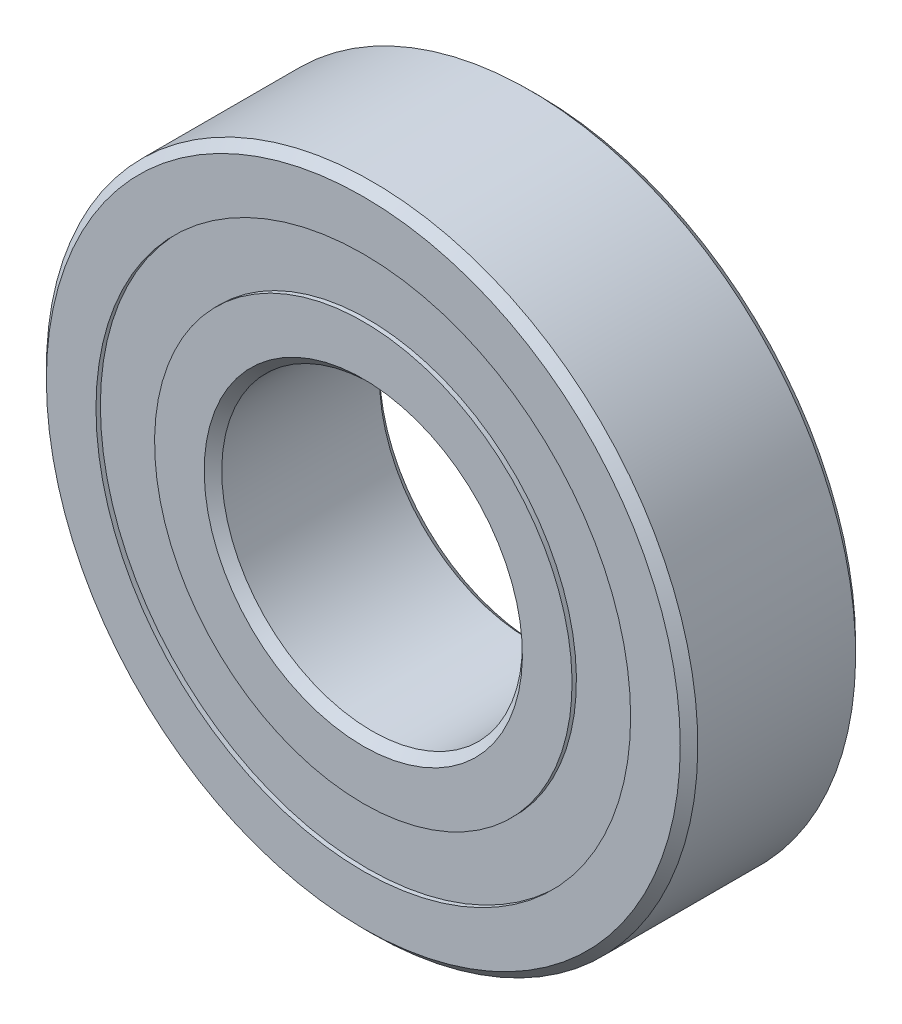
SolidWorks part; units mm, degrees
ref_plane "Front Plane" through (0, 0, 0) normal (0, 0, 1) x (1, 0, 0)
ref_plane "Top Plane" through (0, 0, 0) normal (0, 1, 0) x (1, 0, 0)
ref_plane "Right Plane" through (0, 0, 0) normal (1, 0, 0) x (0, 0, -1)
sketch "Sketch1" plane through (0, 0, 0) normal (0, 0, 1) x (1, 0, 0)
  line L0 (-20.6375, 0) -> (20.6375, 0) construction
  line L1 (-9.525, 0) -> (9.525, 0) construction
  circle A0 centre (0, 0) radius 9.525 construction
  circle A1 centre (0, 0) radius 20.6375 construction
  point P3 (0, 0)
  point P6 (0, 0)
  point P7 (0, -9.525)
  point P11 (0, -20.6375)
  point P12 (0, 9.525)
  point P13 (0, 20.6375)
  dimension "OD" = 41.275
  dimension "ID" = 19.05
sketch "SketchB" plane through (0, 0, 0) normal (1, 0, 0) x (0, 0, -1)
  line L0 (-5.5563, 20.6375) -> (5.5562, 20.6375) construction
  line L1 (0, 20.6375) -> (0, -20.6375) construction
  line L2 (5.0006, 20.6375) -> (-5.0006, 20.6375)
  line L3 (-5.0006, 20.6375) -> (-5.5563, 20.0819)
  line L4 (-5.5563, 20.0819) -> (-5.5563, 16.9374)
  line L5 (-5.5563, 16.9374) -> (-2.4694, 16.9374)
  line L6 (5.5563, 16.9374) -> (2.4694, 16.9374)
  line L7 (5.5562, 20.0819) -> (5.5563, 16.9374)
  line L8 (5.0006, 20.6375) -> (5.5562, 20.0819)
  line L9 (0, 20.6375) -> (0, 15.0813) construction
  line L10 (0, 15.0813) -> (0, 9.525) construction
  line L11 (0, 20.6375) -> (0, -20.6375) construction
  line L12 (-5.5562, 0) -> (5.5562, 0) construction
  line L13 (5.5562, 9.525) -> (-5.5563, 9.525) construction
  line L15 (-5.5562, -9.525) -> (5.5563, -9.525) construction
  arc A0 (-2.4694, 16.9374) -> (2.4694, 16.9374) centre (0, 15.0813) cw
  circle A1 centre (0, 15.0813) radius 3.0892 construction
  point P14 (0, 9.525)
  point P17 (0, 0)
  point P21 (0, 20.6375)
  point P29 (0, 9.525)
  point P30 (0, -9.525)
  dimension "Width" = 11.1125
  dimension "D1" = 45
  dimension "D2" = 0.5556
  dimension "D3" = 4.9389
  dimension "D4" = 1.8562
sketch "Sketch7" plane through (0, 0, 0) normal (1, 0, 0) x (0, 0, -1)
  line L0 (5.0006, 20.6375) -> (5.5562, 20.0819) construction
  line L1 (5.5562, 20.0819) -> (5.5563, 16.9374) construction
  line L2 (5.5563, 16.9374) -> (2.4694, 16.9374) construction
  line L3 (-5.5563, 16.9374) -> (-2.4694, 16.9374) construction
  line L4 (-5.5563, 20.0819) -> (-5.5563, 16.9374) construction
  line L5 (-5.0006, 20.6375) -> (-5.5563, 20.0819) construction
  line L6 (5.0006, 20.6375) -> (-5.0006, 20.6375) construction
  line L7 (5.0006, 20.6375) -> (5.5562, 20.0819)
  line L8 (5.5562, 20.0819) -> (5.5563, 16.9374)
  line L9 (5.5563, 16.9374) -> (2.4694, 16.9374)
  line L10 (-5.5563, 16.9374) -> (-2.4694, 16.9374)
  line L11 (-5.5563, 20.0819) -> (-5.5563, 16.9374)
  line L12 (-5.0006, 20.6375) -> (-5.5563, 20.0819)
  line L13 (5.0006, 20.6375) -> (-5.0006, 20.6375)
  arc A0 (2.4694, 16.9374) -> (-2.4694, 16.9374) centre (0, 15.0813) ccw construction
  arc A1 (2.4694, 16.9374) -> (-2.4694, 16.9374) centre (0, 15.0813) ccw
revolve "Revolve6" add sketch "Sketch7" angle 360 about L12
sketch "Sketch3" plane through (0, 0, 0) normal (1, 0, 0) x (0, 0, -1)
  line L0 (0, 20.6375) -> (0, -20.6375) construction
  line L1 (0, 20.6375) -> (0, -20.6375) construction
  line L2 (-5.0006, 9.525) -> (-5.5563, 10.0806)
  line L3 (-5.5563, 10.0806) -> (-5.5563, 13.2251)
  line L5 (-5.5563, 13.2251) -> (-2.4694, 13.2251)
  line L6 (-5.0006, 9.525) -> (5.0006, 9.525)
  line L8 (5.0006, 9.525) -> (5.5563, 10.0806)
  line L10 (5.5563, 10.0806) -> (5.5563, 13.2251)
  line L11 (5.5563, 13.2251) -> (2.4694, 13.2251)
  line L12 (-5.5563, 20.0819) -> (-5.5563, 16.9374) construction
  line L13 (5.0006, 20.6375) -> (5.5562, 20.0819) construction
  line L15 (5.5563, -20.0819) -> (5.5563, 20.0819) construction
  line L16 (5.0006, 20.6375) -> (5.0006, -20.6375) construction
  arc A1 (2.4694, 13.2251) -> (-2.4694, 13.2251) centre (0, 15.0813) cw
  circle A2 centre (0, 15.0813) radius 3.0892 construction
  point P1 (0, 9.525)
revolve "Revolve3" add sketch "Sketch3" angle 360 about L12
sketch "Sketch4" plane through (0, 0, 0) normal (1, 0, 0) x (0, 0, -1)
  line L0 (-3.0892, 15.0813) -> (3.0892, 15.0813)
  arc A2 (-3.0892, 15.0813) -> (3.0892, 15.0813) centre (0, 15.0813) cw
  arc A3 (2.4694, 16.9374) -> (-2.4694, 16.9374) centre (0, 15.0813) ccw construction
revolve "Revolve4" add sketch "Sketch4" angle 360 about L0
pattern_circular "CirPattern1" count 10 over 360 about axis through (0, 0, 0) along (0, 0, 1) of bodies 104
sketch "Sketch5" plane through (0, 0, 0) normal (1, 0, 0) x (0, 0, -1)
  line L0 (-5.5563, 16.9374) -> (-2.4694, 16.9374) construction
  line L1 (-5.2784, 16.9374) -> (-3.0892, 16.9374)
  line L2 (-5.2784, 16.9374) -> (-5.2784, 13.2251)
  line L3 (-5.2784, 13.2251) -> (-3.0892, 13.2251)
  line L4 (-3.0892, 16.9374) -> (-3.0892, 13.2251)
  line L5 (-5.5563, 13.2251) -> (-2.4694, 13.2251) construction
  line L6 (-5.0006, 20.6375) -> (-5.5563, 20.0819) construction
  line L7 (0, 20.6375) -> (0, 9.525) construction
  line L8 (5.2784, 13.2251) -> (3.0892, 13.2251)
  line L9 (3.0892, 16.9374) -> (3.0892, 13.2251)
  line L10 (5.2784, 16.9374) -> (3.0892, 16.9374)
  line L11 (5.2784, 16.9374) -> (5.2784, 13.2251)
  circle A1 centre (0, 15.0813) radius 3.0892 construction
  point P10 (-5.2784, 20.3597)
revolve "Revolve5" add sketch "Sketch5" angle 360 about L12
equation "\"D2@SketchB\" = \"Width@SketchB\" * .05"
equation "\"D3@SketchB\" = \"Width@SketchB\" / 2.25"
equation "\"D4@SketchB\" =  (  (  ( \"OD@Sketch1\" - \"Width@SketchB\" )  / 2 )  / 3.25 )  / 2.5"
